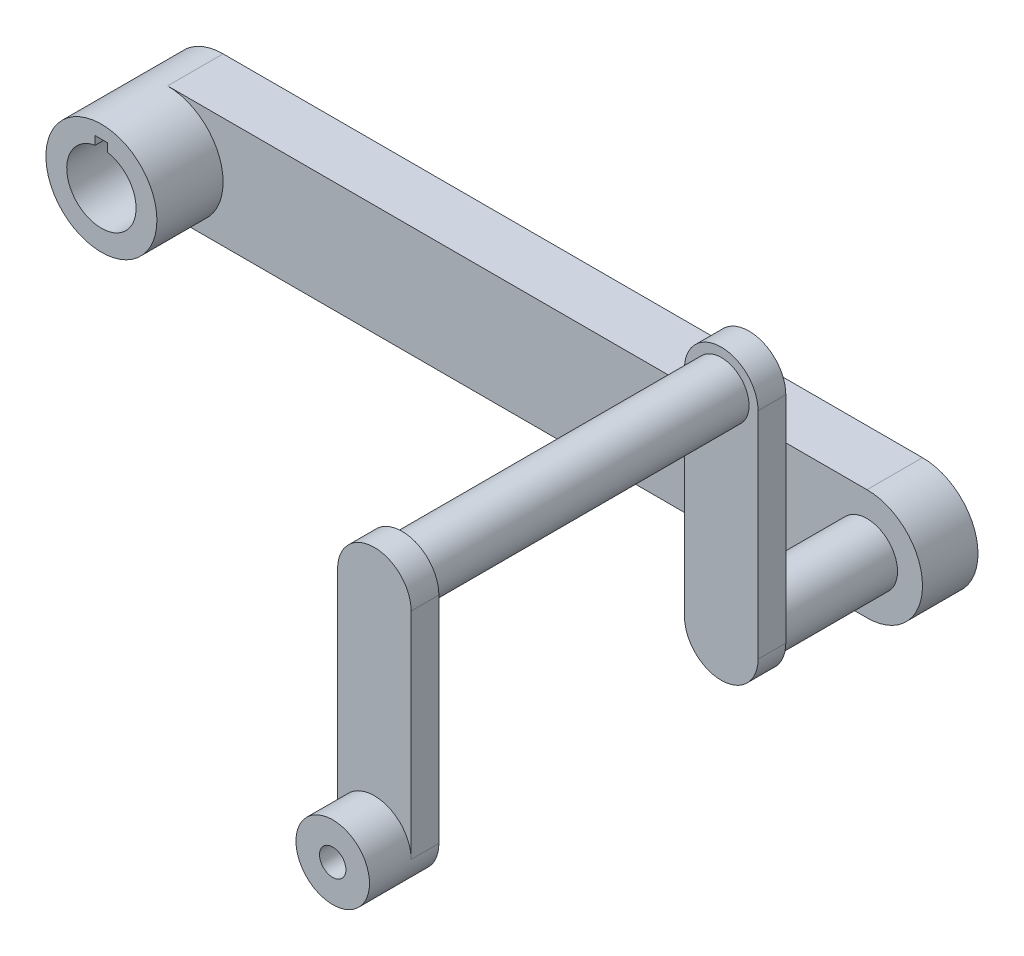
SolidWorks part; units mm, degrees
ref_plane "Alzado" through (0, 0, 0) normal (0, 0, 1) x (1, 0, 0)
ref_plane "Planta" through (0, 0, 0) normal (0, 1, 0) x (1, 0, 0)
ref_plane "Vista lateral" through (0, 0, 0) normal (1, 0, 0) x (0, 0, -1)
sketch "Croquis1" plane through (0, 0, 0) normal (0, 0, 1) x (1, 0, 0)
  line L0 (0, 0) -> (50.4, 0) construction
  line L1 (0, 4) -> (50.4, 4)
  line L2 (0, -4) -> (50.4, -4)
  line L3 (0, 0) -> (0, 2.5) construction
  line L10 (-0.45, 2.4592) -> (-0.45, 3.0592)
  line L11 (-0.45, 3.0592) -> (0.45, 3.0592)
  line L12 (0.45, 2.4592) -> (0.45, 3.0592)
  arc A0 (-0.45, 2.4592) -> (0.45, 2.4592) centre (0, 0) ccw
  arc A1 (0, 4) -> (0, -4) centre (0, 0) ccw
  arc A2 (50.4, -4) -> (50.4, 4) centre (50.4, 0) ccw
  dimension "D2" = 5
  dimension "D3" = 0.9
  dimension "8" = 8
  dimension "D4" = 8
  dimension "D1" = 50.4
  dimension "D5" = 0.45
  dimension "D6" = 0.6
extrude "Saliente-Extruir1" add sketch "Croquis1" against normal blind 4
sketch "Croquis2" plane through (0, 0, 0) normal (0, 0, 1) x (1, 0, 0)
  line L0 (-0.45, 3.0592) -> (-0.45, 2.4592)
  line L1 (0.45, 2.4592) -> (0.45, 3.0592)
  line L2 (0.45, 3.0592) -> (-0.45, 3.0592)
  circle A0 centre (0, 0) radius 4
  arc A1 (-0.45, 2.4592) -> (0.45, 2.4592) centre (0, 0) ccw
extrude "Saliente-Extruir2" add sketch "Croquis2" along normal blind 4.77
sketch "Croquis3" plane through (0, 0, 0) normal (0, 0, 1) x (1, 0, 0)
  circle A0 centre (50.4, 0) radius 2.2
  dimension "D1" = 4.4
extrude "Saliente-Extruir3" add sketch "Croquis3" along normal blind 8.5
sketch "Croquis4" plane through (0, 0, 8.5) normal (0, 0, 1) x (1, 0, 0)
  line L0 (50.4, 0) -> (50.4, 15.5) construction
  line L1 (47.75, 15.5) -> (47.75, 0)
  line L2 (53.05, 15.5) -> (53.05, 0)
  arc A0 (47.75, 0) -> (53.05, 0) centre (50.4, 0) ccw
  arc A1 (53.05, 15.5) -> (47.75, 15.5) centre (50.4, 15.5) ccw
  dimension "D2" = 5.3
  dimension "D1" = 15.5
extrude "Saliente-Extruir4" add sketch "Croquis4" along normal blind 2
sketch "Croquis5" plane through (0, 0, 10.5) normal (0, 0, 1) x (1, 0, 0)
  circle A0 centre (50.4, 15.5) radius 2
extrude "Saliente-Extruir5" add sketch "Croquis5" along normal blind 23
sketch "Croquis6" plane through (0, 0, 33.5) normal (0, 0, 1) x (1, 0, 0)
  line L0 (47.75, 15.5) -> (47.75, 0)
  line L1 (53.05, 15.5) -> (53.05, 0)
  arc A0 (53.05, 15.5) -> (47.75, 15.5) centre (50.4, 15.5) ccw
  circle A1 centre (50.4, 0) radius 0.95
  arc A2 (47.75, 0) -> (53.05, 0) centre (50.4, 0) ccw
  dimension "D1" = 1.9
  dimension "D2" = 5.3
  dimension "D3" = 5.3
extrude "Saliente-Extruir6" add sketch "Croquis6" along normal blind 2
sketch "Croquis7" plane through (0, 0, 35.5) normal (0, 0, 1) x (1, 0, 0)
  circle A0 centre (50.4, 0) radius 0.95
  circle A1 centre (50.4, 0) radius 2.65
  dimension "D1" = 1.9
extrude "Saliente-Extruir7" add sketch "Croquis7" along normal blind 3
sketch "Croquis8" plane through (0, 0, 33.5) normal (0, 0, -1) x (-1, 0, 0)
  circle A0 centre (-50.4, 0) radius 1.25
  dimension "D1" = 2.5
extrude "Cortar-Extruir1" cut sketch "Croquis8" against normal blind 0.5
